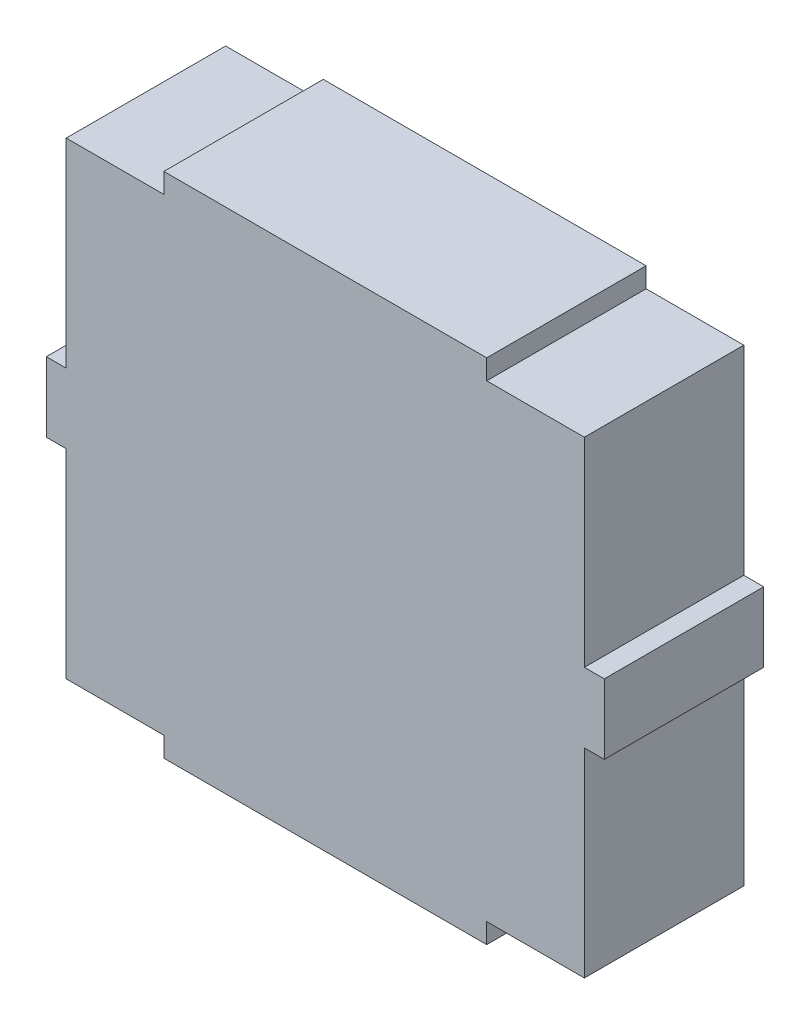
SolidWorks part; units mm, degrees
ref_plane "前视基准面" through (0, 0, 0) normal (0, 0, 1) x (1, 0, 0)
ref_plane "上视基准面" through (0, 0, 0) normal (0, 1, 0) x (1, 0, 0)
ref_plane "右视基准面" through (0, 0, 0) normal (1, 0, 0) x (0, 0, -1)
sketch "草图1" plane through (0, 0, 0) normal (0, 0, 1) x (1, 0, 0)
  line L0 (-1.62, -2.55) -> (-1.62, -2.35)
  line L1 (-1.62, -2.35) -> (-2.6, -2.35)
  line L2 (-2.6, -2.35) -> (-2.6, -2.18)
  line L3 (-2.6, -2.18) -> (-2.6, -0.35)
  line L4 (-2.6, -0.35) -> (-2.8, -0.35)
  line L5 (-2.8, -0.35) -> (-2.8, 0.35)
  line L6 (-2.8, 0.35) -> (-2.6, 0.35)
  line L7 (-2.6, 0.35) -> (-2.6, 2.35)
  line L8 (-2.6, 2.35) -> (-1.62, 2.35)
  line L9 (-1.62, 2.35) -> (-1.62, 2.55)
  line L10 (-1.62, 2.55) -> (1.62, 2.55)
  line L11 (1.62, 2.55) -> (1.62, 2.35)
  line L12 (1.62, 2.35) -> (2.6, 2.35)
  line L13 (2.6, 2.35) -> (2.6, 0.35)
  line L14 (2.6, 0.35) -> (2.8, 0.35)
  line L15 (2.8, 0.35) -> (2.8, -0.35)
  line L16 (2.8, -0.35) -> (2.6, -0.35)
  line L17 (2.6, -0.35) -> (2.6, -2.35)
  line L18 (2.6, -2.35) -> (1.62, -2.35)
  line L19 (1.62, -2.35) -> (1.62, -2.55)
  line L20 (1.62, -2.55) -> (-1.62, -2.55)
extrude "Component_Outline" add sketch "草图1" along normal blind 1.6 separate body
sketch3d "3D草图1"
  line L0 (0, 0, 0) -> (1, 0, 0)
  line L1 (0, 0, 0) -> (0, 1, 0)
  line L2 (0, 0, 0) -> (0, 0, 1)
  point P0 (0, 0, 0)
